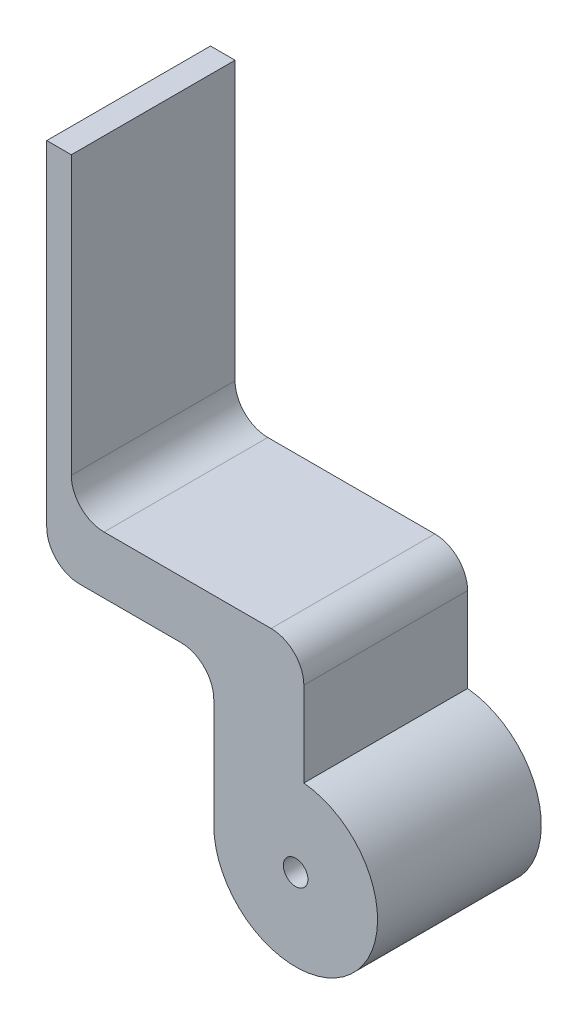
SolidWorks part; units mm, degrees
ref_plane "Front Plane" through (0, 0, 0) normal (0, 0, 1) x (1, 0, 0)
ref_plane "Top Plane" through (0, 0, 0) normal (0, 1, 0) x (1, 0, 0)
ref_plane "Right Plane" through (0, 0, 0) normal (1, 0, 0) x (0, 0, -1)
sketch "Sketch1" plane through (0, 0, 0) normal (0, 0, 1) x (1, 0, 0)
  line L4 (-14, 17.3) -> (-26.4, 17.3)
  line L5 (-30.4, 21.3) -> (-30.4, 62.2055)
  line L6 (-30.4, 62.2055) -> (-27.4, 62.2055)
  line L7 (-27.4, 62.2055) -> (-27.4, 28.3)
  line L8 (-23.4, 24.3) -> (-3, 24.3)
  line L9 (1, 20.3) -> (1, 9.9499)
  line L10 (-10, 13.3) -> (-10, 0)
  arc A0 (-10, 0) -> (1, 9.9499) centre (0, 0) ccw
  arc A1 (1, 20.3) -> (-3, 24.3) centre (-3, 20.3) ccw
  arc A2 (-10, 13.3) -> (-14, 17.3) centre (-14, 13.3) ccw
  arc A3 (-27.4, 28.3) -> (-23.4, 24.3) centre (-23.4, 28.3) ccw
  arc A4 (-30.4, 21.3) -> (-26.4, 17.3) centre (-26.4, 21.3) ccw
  point P9 (-10, 17.3)
  dimension "D1" = 20
  dimension "D6" = 4
  dimension "D7" = 4
  dimension "D8" = 4
  dimension "D10" = 4
  dimension "D2" = 7
  dimension "D3" = 17.3
  dimension "D4" = 44.9055
  dimension "D5" = 11
  dimension "D9" = 3
extrude "Boss-Extrude2" add sketch "Sketch1" along normal blind 20
sketch "Sketch2" plane through (0, 0, 20) normal (0, 0, 1) x (1, 0, 0)
  line L0 (1, 9.9499) -> (1, 20.3) construction
  line L1 (-3, 24.3) -> (-23.4, 24.3) construction
  circle A1 centre (0, 0) radius 1.5
  dimension "D1" = 3
  dimension "D2" = 1
  dimension "D3" = 24.3
extrude "Cut-Extrude1" cut sketch "Sketch2" against normal blind 30
